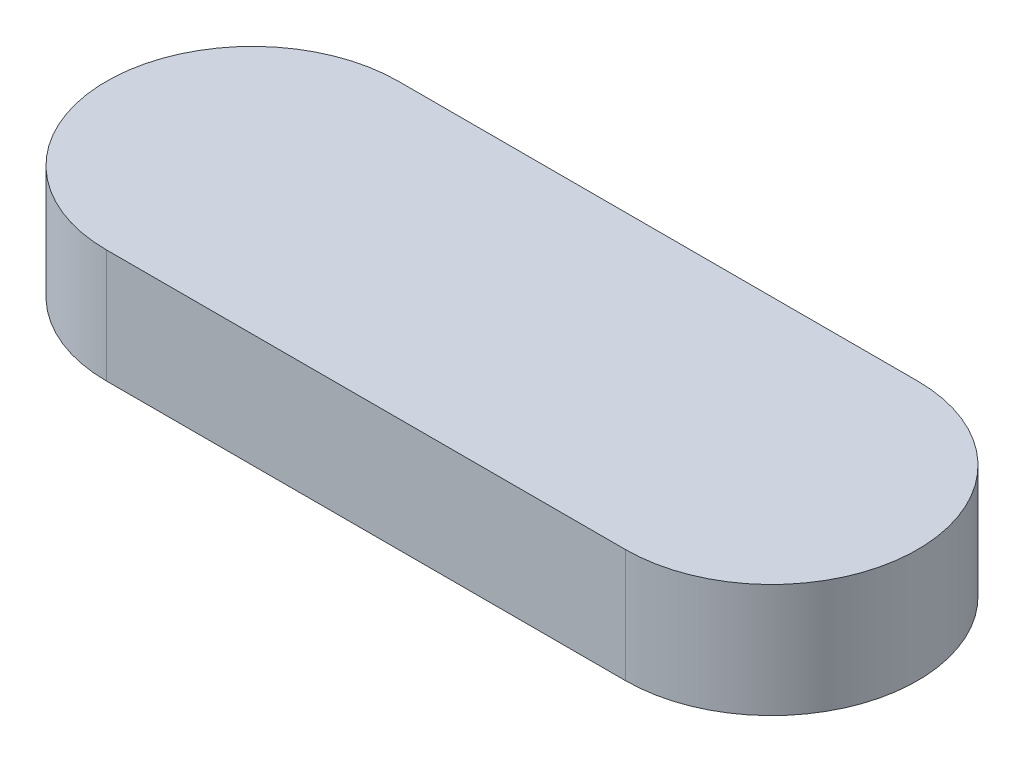
SolidWorks part; units mm, degrees
ref_plane "Front Plane" through (0, 0, 0) normal (0, 0, 1) x (1, 0, 0)
ref_plane "Top Plane" through (0, 0, 0) normal (0, 1, 0) x (1, 0, 0)
ref_plane "Right Plane" through (0, 0, 0) normal (1, 0, 0) x (0, 0, -1)
sketch "Sketch1" plane through (0, 0, 0) normal (0, 1, 0) x (1, 0, 0)
  line L0 (16, 0) -> (-16, 0) construction
  line L1 (16, -9) -> (-16, -9)
  line L2 (16, 9) -> (-16, 9)
  arc A0 (16, -9) -> (16, 9) centre (16, 0) ccw
  arc A1 (-16, 9) -> (-16, -9) centre (-16, 0) ccw
  point P2 (0, 0)
  dimension "D2" = 9
  dimension "D1" = 32
extrude "Boss-Extrude1" add sketch "Sketch1" along normal blind 7
